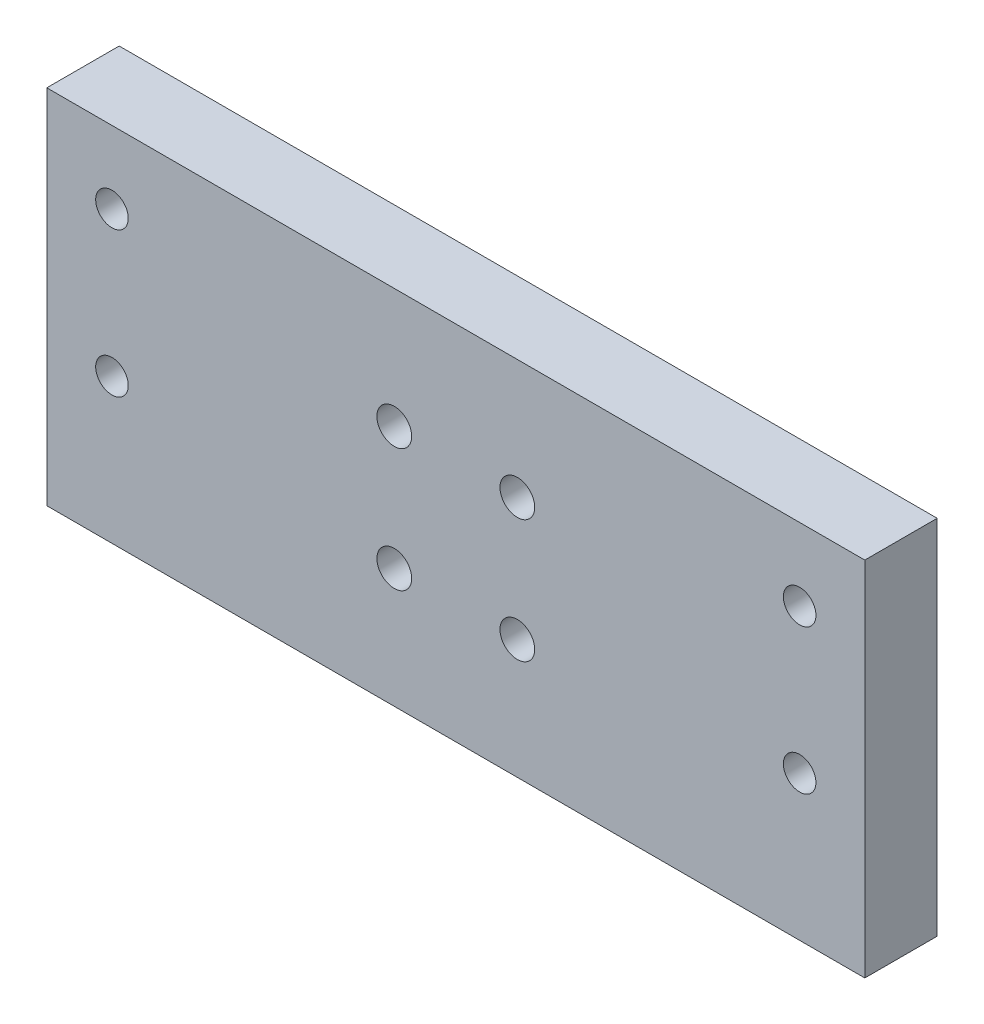
SolidWorks part; units mm, degrees
ref_plane "Front Plane" through (0, 0, 0) normal (0, 0, 1) x (1, 0, 0)
ref_plane "Top Plane" through (0, 0, 0) normal (0, 1, 0) x (1, 0, 0)
ref_plane "Right Plane" through (0, 0, 0) normal (1, 0, 0) x (0, 0, -1)
sketch "Sketch1" plane through (0, 0, 0) normal (0, 0, 1) x (1, 0, 0)
  line L0 (-28.9576, 0) -> (27.267, 0) construction
  line L1 (-56.5, -25) -> (56.5, -25)
  line L2 (-56.5, -25) -> (-56.5, 25)
  line L3 (-56.5, 25) -> (56.5, 25)
  line L4 (56.5, -25) -> (56.5, 25)
  line L5 (-56.5, -25) -> (56.5, 25) construction
  line L6 (-56.5, 25) -> (56.5, -25) construction
  line L7 (-8.5, -8.5) -> (8.5, -8.5) construction
  line L8 (-8.5, -8.5) -> (-8.5, 8.5) construction
  line L9 (-8.5, 8.5) -> (8.5, 8.5) construction
  line L10 (8.5, -8.5) -> (8.5, 8.5) construction
  line L11 (-8.5, -8.5) -> (8.5, 8.5) construction
  line L12 (-8.5, 8.5) -> (8.5, -8.5) construction
  line L13 (0, 21.7913) -> (0, -17.8484) construction
  point P0 (0, 0)
  point P6 (0, 0)
  dimension "D1" = 113
  dimension "D2" = 50
  dimension "D3" = 17
extrude "Boss-Extrude1" add sketch "Sketch1" along normal blind 10
hole_wizard "CBORE for M4 SHCS1" positions "Sketch2" profile "Sketch3" counterbore size "M4" standard "ANSI Metric" end condition up to next
sketch "Sketch2" plane through (0, 0, 0) normal (0, 0, -1) x (-1, 0, 0)
  line L0 (8.5, -8.5) -> (-8.5, 8.5) construction
  line L1 (8.5, -8.5) -> (8.5, 8.5) construction
  point P0 (-8.5, 8.5)
  point P4 (-8.5, -8.5)
  point P7 (8.5, -8.5)
  point P10 (8.5, 8.5)
  point P15 (-6.2304, 6.2304)
  point P17 (8.5, 2.8881)
sketch "Sketch3" plane through (8.5, 8.5, 0) normal (1, 0, 0) x (0, 1, 0)
  line L0 (0, 0) -> (0, 10)
  line L1 (0, 10) -> (2.4, 10)
  line L3 (2.4, 10) -> (2.4, 4)
  line L4 (2.4, 4) -> (4, 4)
  line L5 (4, 4) -> (4, 0)
  line L7 (4, 0) -> (0, 0)
  line L11 (0, -6.35) -> (0, 107.95) construction
  dimension "Thru Hole Dia." = 4.8
  dimension "Thru Hole Depth" = 10
  dimension "C'Bore Dia." = 8
  dimension "C'Bore Depth" = 4
sketch "Sketch4" plane through (0, 0, 0) normal (0, 0, -1) x (-1, 0, 0)
  line L0 (-56.5, -25) -> (-56.5, 25) construction
  line L1 (-56.5, 25) -> (-38.5, 25) construction
  line L2 (-56.5, 25) -> (-56.5, -15) construction
  line L3 (-56.5, -15) -> (-38.5, -15) construction
  line L4 (-38.5, 25) -> (-38.5, -15) construction
  line L5 (-47.5, 25) -> (-47.5, -15) construction
  line L6 (56.5, 25) -> (-56.5, 25) construction
  line L7 (0, 43.2506) -> (0, -38.9135) construction
  line L8 (47.5, 25) -> (47.5, -15) construction
  line L9 (38.5, 25) -> (38.5, -15) construction
  line L10 (56.5, -15) -> (38.5, -15) construction
  line L11 (56.5, 25) -> (56.5, -15) construction
  line L12 (56.5, 25) -> (38.5, 25) construction
  circle A0 centre (-47.5, 15) radius 2.25
  circle A1 centre (-47.5, -5) radius 2.25
  circle A2 centre (47.5, -5) radius 2.25
  circle A3 centre (47.5, 15) radius 2.25
  point P8 (-47.5, 15)
  point P9 (-47.5, -5)
  point P19 (-47.5, -5)
  dimension "D5" = 4.5
  dimension "D1" = 18
  dimension "D2" = 40
  dimension "D3" = 20
  dimension "D4" = 10
extrude "Cut-Extrude1" cut sketch "Sketch4" against normal through all
